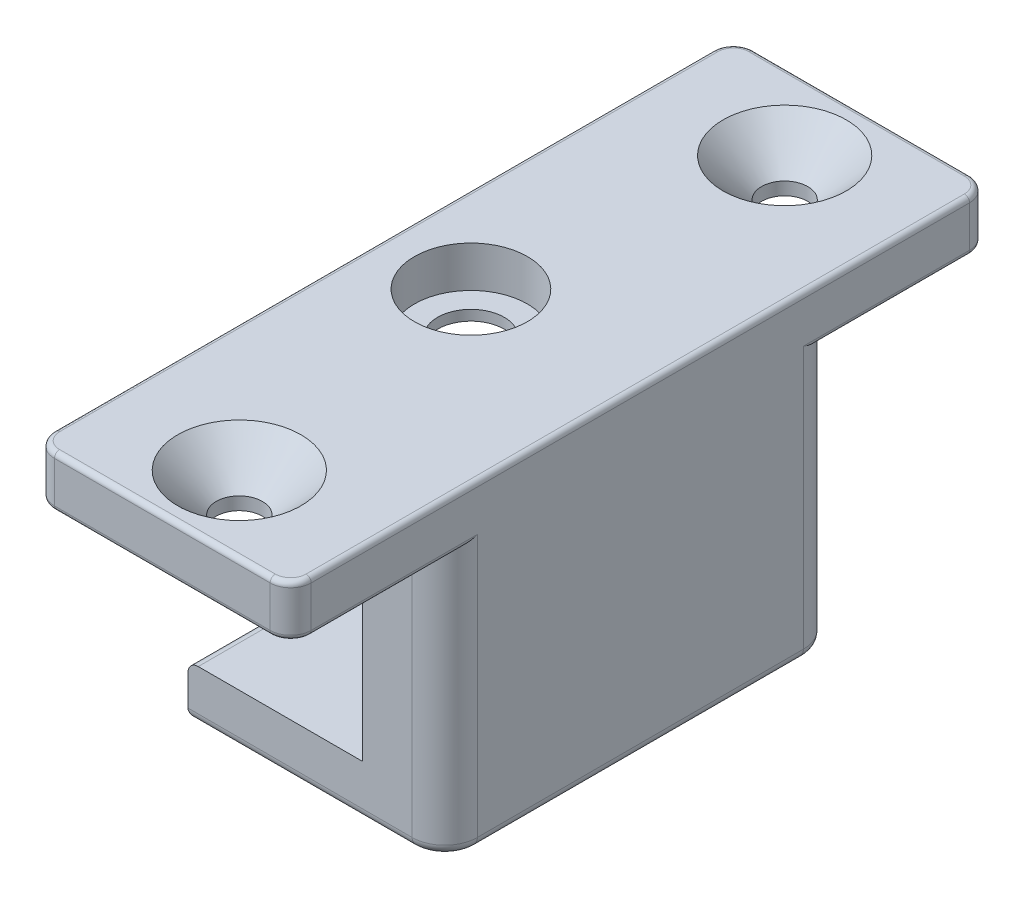
SolidWorks part; units mm, degrees
material "ABS"
ref_plane "Front Plane" through (0, 0, 0) normal (0, 0, 1) x (1, 0, 0)
ref_plane "Top Plane" through (0, 0, 0) normal (0, 1, 0) x (1, 0, 0)
ref_plane "Right Plane" through (0, 0, 0) normal (1, 0, 0) x (0, 0, -1)
sketch "Sketch1" plane through (0, 0, 0) normal (0, 1, 0) x (1, 0, 0)
  line L1 (-12.5, 34.05) -> (12.5, 34.05)
  line L2 (-12.5, 34.05) -> (-12.5, -34.05)
  line L3 (-12.5, -34.05) -> (12.5, -34.05)
  line L4 (12.5, 34.05) -> (12.5, -34.05)
  line L5 (-12.5, 34.05) -> (12.5, -34.05) construction
  line L6 (-12.5, -34.05) -> (12.5, 34.05) construction
  point P0 (0, 0)
  dimension "D1" = 68.1
  dimension "D2" = 25
extrude "Boss-Extrude1" add sketch "Sketch1" against normal blind 31.05
sketch "Sketch2" plane through (12.5, 0, 0) normal (1, 0, 0) x (0, 0, -1)
  line L0 (0, 0) -> (0, -31.05) construction
  line L1 (-34.05, 0) -> (34.05, 0) construction
  line L2 (-34.05, -31.05) -> (34.05, -31.05) construction
  line L3 (-34.05, -5) -> (-19.05, -5)
  line L4 (-34.05, -31.05) -> (-34.05, 0) construction
  line L5 (-19.05, -5) -> (-19.05, -31.05)
  line L6 (-19.05, -31.05) -> (-34.05, -31.05)
  line L7 (-34.05, -31.05) -> (-34.05, -5)
  line L8 (34.05, -5) -> (19.05, -5)
  line L9 (34.05, -31.05) -> (34.05, 0) construction
  line L10 (19.05, -5) -> (19.05, -31.05)
  line L11 (19.05, -31.05) -> (34.05, -31.05)
  line L12 (34.05, -31.05) -> (34.05, -5)
  dimension "D1" = 5
  dimension "D2" = 19.05
extrude "Cut-Extrude1" cut sketch "Sketch2" against normal up to next
sketch "Sketch3" plane through (0, 0, 0) normal (0, 0, 1) x (1, 0, 0)
  line L0 (-12.5, -5) -> (4.5, -5)
  line L1 (4.5, -5) -> (4.5, -26.05)
  line L2 (4.5, -26.05) -> (-12.5, -26.05)
  line L3 (-12.5, -26.05) -> (-12.5, -5)
  line L4 (-12.5, -31.05) -> (-12.5, -5) construction
  line L7 (-12.5, -5) -> (12.5, -5) construction
  line L10 (-12.5, -31.05) -> (12.5, -31.05) construction
  dimension "D1" = 17
  dimension "D2" = 5
extrude "Cut-Extrude2" cut sketch "Sketch3" along normal mid plane 50
sketch "Sketch4" plane through (0, 0, 0) normal (0, 1, 0) x (1, 0, 0)
  line L0 (-12.5, 0) -> (4.5, 0) construction
  line L1 (-12.5, 34.05) -> (-12.5, -34.05) construction
  line L2 (4.5, -19.05) -> (4.5, 19.05) construction
  line L3 (0, -19.05) -> (0, -34.05) construction
  line L4 (-12.5, -34.05) -> (12.5, -34.05) construction
  line L5 (4.5, -19.05) -> (12.5, -19.05) construction
  point P8 (-4, 0)
  point P15 (0, -26.55)
sketch "Sketch5" plane through (0, 0, 0) normal (1, 0, 0) x (0, 0, -1)
  line L0 (-32.55, 0) -> (-28.8, -3.75)
  line L1 (-19.05, 0) -> (-34.05, 0) construction
  line L2 (-28.8, -3.75) -> (-28.8, -5)
  line L3 (-28.8, -5) -> (-26.55, -5)
  line L4 (-26.55, -5) -> (-26.55, 0)
  line L5 (-26.55, 0) -> (-32.55, 0)
  line L6 (34.05, -5) -> (-34.05, -5) construction
  dimension "D1" = 45
  dimension "D2" = 2.25
  dimension "D3" = 6
revolve "Cut-Revolve1" cut sketch "Sketch5" angle 360 about L4
mirror "Mirror1" about plane through (0, 0, 0) normal (0, 0, 1) of "Cut-Revolve1"
sketch "Sketch6" plane through (0, 0, 0) normal (0, 0, 1) x (1, 0, 0)
  line L0 (-4, 0) -> (-4, -5)
  line L1 (-12.5, 0) -> (4.5, 0) construction
  line L2 (-4, -5) -> (-0.75, -5)
  line L3 (-0.75, -5) -> (-0.75, -4)
  line L4 (-0.75, -4) -> (1.5, -4)
  line L5 (1.5, -4) -> (1.5, 0)
  line L6 (1.5, 0) -> (-4, 0)
  line L7 (-12.5, -5) -> (12.5, -5) construction
  dimension "D1" = 4
  dimension "D2" = 3.25
  dimension "D3" = 5.5
revolve "Cut-Revolve2" cut sketch "Sketch6" angle 360 about L0
fillet "Fillet5" radius 3.175 2 edges at (12.5, -18.025, 19.05) (12.5, -18.025, -19.05)
fillet "Fillet2" radius 1 7 edges at (-12.5, -26.05, 0) (-12.5, -31.05, 0) (12.5, -31.05, 0) (-1.5875, -31.05, 19.05) (11.5701, -31.05, 18.1201) (-1.5875, -31.05, -19.05) (11.5701, -31.05, -18.1201)
fillet "Fillet6" radius 2 4 edges at (12.5, -2.5, 34.05) (-12.5, -2.5, 34.05) (12.5, -2.5, -34.05) (-12.5, -2.5, -34.05)
fillet "Fillet3" radius 0.5 17 edges at (0, 0, 34.05) (0, -5, 34.05) (-12.5, 0, 0) (0, 0, -34.05) (-12.5, -5, 0) (0, -5, -34.05) (11.9142, 0, -33.4642) (12.5, 0, 0) (11.9142, 0, 33.4642) (-11.9142, 0, 33.4642) (-11.9142, 0, -33.4642) (12.5, -5, 23.9625) (11.9142, -5, 33.4642) (-11.9142, -5, 33.4642) (-11.9142, -5, -33.4642) (12.5, -5, -23.9625) (11.9142, -5, -33.4642)
